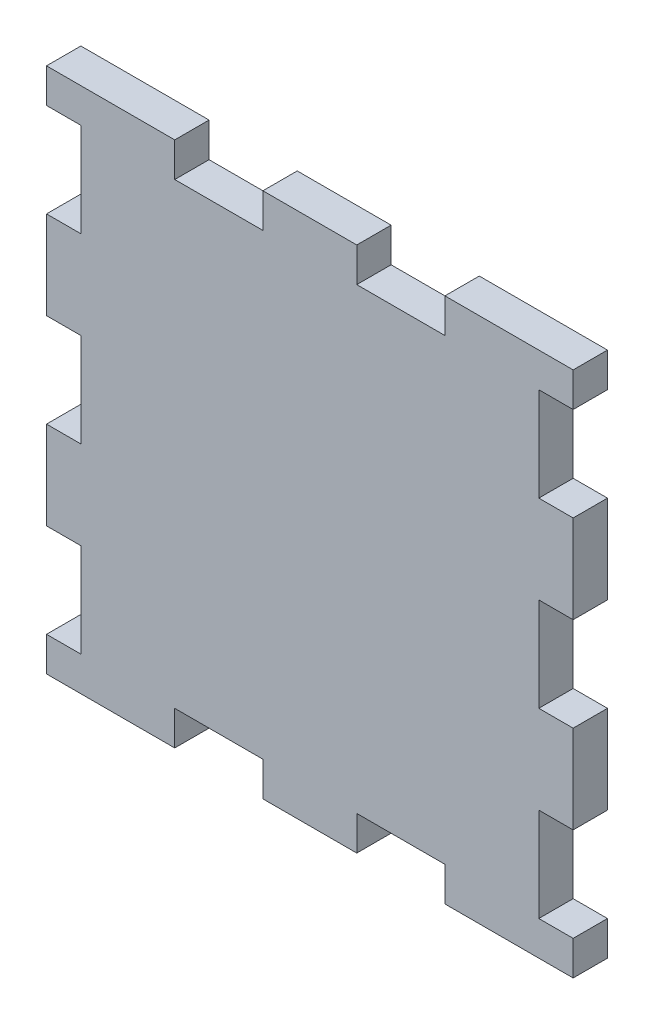
SolidWorks part; units mm, degrees
ref_plane "Alzado" through (0, 0, 0) normal (0, 0, 1) x (1, 0, 0)
ref_plane "Planta" through (0, 0, 0) normal (0, 1, 0) x (1, 0, 0)
ref_plane "Vista lateral" through (0, 0, 0) normal (1, 0, 0) x (0, 0, -1)
sketch "Croquis1" plane through (0, 0, 0) normal (0, 0, 1) x (1, 0, 0)
  line L0 (0, 0) -> (0, 14.5855) construction
  line L1 (20, -20) -> (-20, -20)
  line L2 (20, -20) -> (20, 20)
  line L3 (20, 20) -> (-20, 20)
  line L4 (-20, -20) -> (-20, 20)
  line L5 (20, -20) -> (-20, 20) construction
  line L6 (20, 20) -> (-20, -20) construction
  line L7 (-11.8, 20) -> (-23, 20)
  line L8 (-11.8, 20) -> (-11.8, 23)
  line L9 (-11.8, 23) -> (-23, 23)
  line L10 (-23, 20) -> (-23, 23)
  line L11 (11.8, 20) -> (23, 20)
  line L12 (11.8, 20) -> (11.8, 23)
  line L13 (11.8, 23) -> (23, 23)
  line L14 (23, 20) -> (23, 23)
  line L15 (-4.1, 20) -> (4.1, 20)
  line L16 (-4.1, 20) -> (-4.1, 23)
  line L17 (-4.1, 23) -> (4.1, 23)
  line L18 (4.1, 20) -> (4.1, 23)
  line L19 (0, 0) -> (-13.2385, 0) construction
  line L20 (11.8, -23) -> (23, -23)
  line L21 (-20, 11.8) -> (-23, 11.8)
  line L22 (-20, 11.8) -> (-20, 4.1)
  line L23 (-20, 4.1) -> (-23, 4.1)
  line L24 (-23, 11.8) -> (-23, 4.1)
  line L25 (-20, -4.1) -> (-23, -4.1)
  line L26 (-20, -4.1) -> (-20, -11.8)
  line L27 (-20, -11.8) -> (-23, -11.8)
  line L28 (-23, -4.1) -> (-23, -11.8)
  line L29 (23, -20) -> (23, -23)
  line L30 (11.8, -20) -> (23, -20)
  line L31 (11.8, -20) -> (11.8, -23)
  line L32 (-4.1, -23) -> (4.1, -23)
  line L33 (4.1, -20) -> (4.1, -23)
  line L34 (-4.1, -20) -> (4.1, -20)
  line L35 (-4.1, -20) -> (-4.1, -23)
  line L36 (-11.8, -23) -> (-23, -23)
  line L37 (-23, -20) -> (-23, -23)
  line L38 (-11.8, -20) -> (-23, -20)
  line L39 (-11.8, -20) -> (-11.8, -23)
  line L40 (20, -11.8) -> (23, -11.8)
  line L41 (23, -4.1) -> (23, -11.8)
  line L42 (20, -4.1) -> (23, -4.1)
  line L43 (20, -4.1) -> (20, -11.8)
  line L44 (20, 4.1) -> (23, 4.1)
  line L45 (23, 11.8) -> (23, 4.1)
  line L46 (20, 11.8) -> (23, 11.8)
  line L47 (20, 11.8) -> (20, 4.1)
  point P0 (0, 0)
  dimension "D1" = 40
  dimension "D2" = 40
  dimension "D3" = 7.7
  dimension "D4" = 8.2
  dimension "D5" = 7.7
  dimension "D6" = 11.2
  dimension "D7" = 11.2
  dimension "D8" = 3
  dimension "D9" = 3
  dimension "D10" = 3
  dimension "D11" = 3
  dimension "D12" = 3
  dimension "D13" = 3
  dimension "D14" = 8.2
  dimension "D15" = 8.2
  dimension "D16" = 7.7
  dimension "D17" = 8.2
extrude "Saliente-Extruir1" add sketch "Croquis1" along normal blind 3 contours L10 L7 L3 L8 L9 | L3 L18 L17 L16 | L11 L14 L13 L12 L3 | L46 L2 L44 L45 | L42 L2 L40 L41 | L1 L31 L20 L29 L30 | L1 L35 L32 L33 | L39 L1 L38 L37 L36 | L21 L24 L23 L4 | L4 L1 L2 L3 | L28 L27 L26 L25
